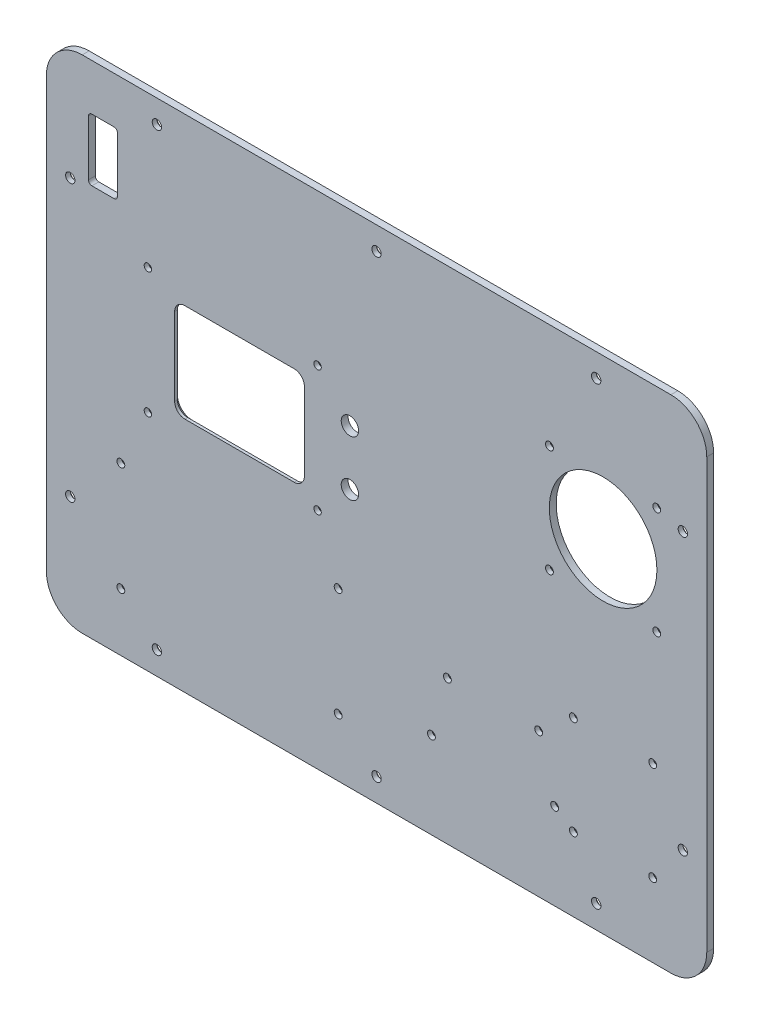
SolidWorks part; units mm, degrees
ref_plane "Front Plane" through (0, 0, 0) normal (0, 0, 1) x (1, 0, 0)
ref_plane "Top Plane" through (0, 0, 0) normal (0, 1, 0) x (1, 0, 0)
ref_plane "Right Plane" through (0, 0, 0) normal (1, 0, 0) x (0, 0, -1)
sketch "Sketch1" plane through (0, 0, 0) normal (0, 0, 1) x (1, 0, 0)
  line L0 (-151.9669, 98.7552) -> (-151.9669, -98.7552) construction
  line L1 (-135.4569, -115.2652) -> (135.4569, -115.2652) construction
  line L2 (151.9669, -98.7552) -> (151.9669, 98.7552) construction
  line L3 (135.4569, 115.2652) -> (-135.4569, 115.2652) construction
  line L4 (0, 115.2652) -> (0, 0) construction
  line L5 (0, 0) -> (151.9669, 0) construction
  line L25 (-151.9669, 98.7552) -> (-151.9669, -98.7552)
  line L27 (-135.4569, -115.2652) -> (135.4569, -115.2652)
  line L29 (151.9669, -98.7552) -> (151.9669, 98.7552)
  line L31 (135.4569, 115.2652) -> (-135.4569, 115.2652)
  arc A0 (-135.4569, -115.2652) -> (-151.9669, -98.7552) centre (-135.4569, -98.7552) cw
  arc A1 (135.4569, -115.2652) -> (151.9669, -98.7552) centre (135.4569, -98.7552) ccw
  arc A2 (151.9669, 98.7552) -> (135.4569, 115.2652) centre (135.4569, 98.7552) ccw
  arc A3 (-151.9669, 98.7552) -> (-135.4569, 115.2652) centre (-135.4569, 98.7552) cw
  arc A4 (-135.4569, -115.2652) -> (-151.9669, -98.7552) centre (-135.4569, -98.7552) cw construction
  arc A5 (135.4569, -115.2652) -> (151.9669, -98.7552) centre (135.4569, -98.7552) ccw construction
  arc A6 (151.9669, 98.7552) -> (135.4569, 115.2652) centre (135.4569, 98.7552) ccw construction
  arc A7 (-151.9669, 98.7552) -> (-135.4569, 115.2652) centre (-135.4569, 98.7552) cw construction
  dimension "D1" = 16.51
  dimension "D3" = 230.5304
  dimension "D4" = 303.9339
  dimension "D2" = 0
extrude "Boss-Extrude1" add sketch "Sketch1" against normal blind 3.175
hole_wizard "#6 Clearance Hole1" positions "Sketch2" profile "Sketch3" hole size "#6" standard "ANSI Inch" end condition up to next
sketch "Sketch2" plane through (0, 0, 0) normal (0, 0, 1) x (1, 0, 0)
  line L3 (140.9687, 63.5) -> (140.9687, -63.5) construction
  line L6 (-101.092, 104.648) -> (101.092, 104.648) construction
  line L9 (-140.9687, 63.5) -> (-140.9687, -63.5) construction
  line L10 (-101.092, -104.648) -> (101.092, -104.648) construction
  line L13 (0, -104.648) -> (0, 0) construction
  line L14 (0, 0) -> (140.9687, 0) construction
  line L17 (0, 104.648) -> (0, 0) construction
  line L18 (0, 0) -> (-140.9687, 0) construction
  point P38 (101.092, 104.648)
  point P40 (-101.092, 104.648)
  point P42 (-140.9687, 63.5)
  point P44 (-140.9687, -63.5)
  point P48 (101.092, -104.648)
  point P50 (140.9687, -63.5)
  point P52 (140.9687, 63.5)
  point P108 (-101.092, -104.648)
  point P117 (0, -104.648)
  point P125 (0, 104.648)
  dimension "D1" = 104.648
  dimension "D2" = 140.9687
  dimension "D3" = 104.648
  dimension "D4" = 140.9687
  dimension "D5" = 127
  dimension "D6" = 127
  dimension "D7" = 202.184
  dimension "D8" = 202.184
sketch "Sketch3" plane through (101.092, 104.648, 0) normal (1, 0, 0) x (0, -1, 0)
  line L0 (0, 0) -> (0, 3.175)
  line L1 (0, 3.175) -> (3.3655, 3.175)
  line L2 (2.1526, 2.1573) -> (2.1526, 0)
  line L5 (2.1526, 0) -> (0, 0)
  line L7 (3.3655, 3.175) -> (2.1526, 2.1573)
  line L8 (-3.3655, 3.175) -> (-2.1527, 2.1573) construction
  line L11 (0, -6.35) -> (0, 107.95) construction
  dimension "Thru Hole Dia." = 4.3053
  dimension "Thru Hole Depth" = 3.175
  dimension "Far C'Sink Dia." = 6.731
  dimension "Far C'Sink Angle" = 100
sketch "Sketch23" plane through (0, 0, 0) normal (0, 0, 1) x (1, 0, 0)
  line L0 (135.4569, 115.2652) -> (-135.4569, 115.2652) construction
  line L1 (151.9669, -98.7552) -> (151.9669, 98.7552) construction
  circle A0 centre (104.2657, 42.164) radius 24.765
  dimension "D1" = 49.53
  dimension "D2" = 73.1012
  dimension "D3" = 47.7012
extrude "Cut-Extrude10" cut sketch "Sketch23" against normal through all
sketch "Sketch24" plane through (0, 0, 0) normal (0, 0, 1) x (1, 0, 0)
  line L1 (-92.9119, 38.9204) -> (-33.2219, 38.9204)
  line L2 (-92.9119, 38.9204) -> (-92.9119, -6.2916)
  line L3 (-92.9119, -6.2916) -> (-33.2219, -6.2916)
  line L4 (-33.2219, 38.9204) -> (-33.2219, -6.2916)
  line L5 (-92.9119, 38.9204) -> (-33.2219, -6.2916) construction
  line L7 (-151.9669, 98.7552) -> (-151.9669, -98.7552) construction
  line L8 (-135.4569, -115.2652) -> (135.4569, -115.2652) construction
  point P4 (-63.0669, 16.3144)
  dimension "D1" = 88.9
  dimension "D2" = 131.5796
  dimension "D3" = 59.69
  dimension "D4" = 45.212
extrude "Cut-Extrude11" cut sketch "Sketch24" against normal through all
fillet "Fillet2" radius 4.699 4 edges at (-33.2219, -6.2916, -1.5875) (-92.9119, -6.2916, -1.5875) (-92.9119, 38.9204, -1.5875) (-33.2219, 38.9204, -1.5875)
chamfer "Chamfer1" distance 1.905 angle 45 8 edges at (-63.0669, -6.2916, -3.175) (-92.9119, 16.3144, -3.175) (-63.0669, 38.9204, -3.175) (-33.2219, 16.3144, -3.175) (-91.5356, -4.9153, -3.175) (-91.5356, 37.5441, -3.175) (-34.5982, -4.9153, -3.175) (-34.5982, 37.5441, -3.175)
hole_wizard "M3 Clearance Hole3" positions "Sketch29" profile "Sketch30" hole size "M3" standard "ANSI Metric" end condition up to next
sketch "Sketch29" plane through (0, 0, 0) normal (0, 0, 1) x (1, 0, 0)
  line L1 (79.57, 66.8597) -> (128.9614, 66.8597) construction
  line L2 (79.57, 66.8597) -> (79.57, 17.4683) construction
  line L3 (79.57, 17.4683) -> (128.9614, 17.4683) construction
  line L4 (128.9614, 66.8597) -> (128.9614, 17.4683) construction
  line L5 (104.2657, 66.8597) -> (104.2657, 17.4683) construction
  circle A2 centre (104.2657, 42.164) radius 34.925
  circle A3 centre (104.2657, 42.164) radius 24.765 construction
  point P0 (79.57, 66.8597)
  point P2 (128.9614, 66.8597)
  point P4 (128.9614, 17.4683)
  point P6 (79.57, 17.4683)
  dimension "D1" = 69.85
sketch "Sketch30" plane through (79.57, 66.8597, 0) normal (1, 0, 0) x (0, -1, 0)
  line L0 (0, 0) -> (0, 3.175)
  line L1 (0, 3.175) -> (2.85, 3.175)
  line L2 (1.8, 2.125) -> (1.8, 0)
  line L5 (1.8, 0) -> (0, 0)
  line L7 (2.85, 3.175) -> (1.8, 2.125)
  line L8 (-2.85, 3.175) -> (-1.8, 2.125) construction
  line L11 (0, -6.35) -> (0, 107.95) construction
  dimension "Thru Hole Dia." = 3.6
  dimension "Thru Hole Depth" = 3.175
  dimension "Far C'Sink Dia." = 5.7
  dimension "Far C'Sink Angle" = 90
hole_wizard "M3 Clearance Hole1" positions "Sketch31" profile "Sketch32" hole size "M3" standard "ANSI Metric" end condition up to next
sketch "Sketch31" plane through (0, 0, -3.175) normal (0, 0, -1) x (-1, 0, 0)
  line L1 (17.6769, -38.5952) -> (117.6769, -38.5952) construction
  line L2 (17.6769, -38.5952) -> (17.6769, -88.5952) construction
  line L3 (17.6769, -88.5952) -> (117.6769, -88.5952) construction
  line L4 (117.6769, -38.5952) -> (117.6769, -88.5952) construction
  line L5 (151.9669, 98.7552) -> (151.9669, -98.7552) construction
  line L6 (135.4569, -115.2652) -> (-135.4569, -115.2652) construction
  point P0 (17.6769, -38.5952)
  point P2 (117.6769, -38.5952)
  point P4 (117.6769, -88.5952)
  point P6 (17.6769, -88.5952)
  dimension "D1" = 100
  dimension "D2" = 50
  dimension "D3" = 34.29
  dimension "D4" = 26.67
sketch "Sketch32" plane through (-17.6769, -38.5952, -3.175) normal (1, 0, 0) x (0, 1, 0)
  line L0 (0, 0) -> (0, 3.175)
  line L1 (0, 3.175) -> (1.8, 3.175)
  line L2 (1.8, 3.175) -> (1.8, 1.05)
  line L3 (1.8, 1.05) -> (2.85, 0)
  line L5 (2.85, 0) -> (0, 0)
  line L6 (-1.8, 1.05) -> (-2.85, 0) construction
  line L11 (0, -6.35) -> (0, 107.95) construction
  dimension "Thru Hole Dia." = 3.6
  dimension "Thru Hole Depth" = 3.175
  dimension "Near C'Sink Dia." = 5.7
  dimension "Near C'Sink Angle" = 90
hole_wizard "M3 Clearance Hole2" positions "Sketch33" profile "Sketch34" hole size "M3" standard "ANSI Metric" end condition up to next
sketch "Sketch33" plane through (0, 0, 0) normal (0, 0, 1) x (1, 0, 0)
  line L0 (-135.4569, -115.2652) -> (135.4569, -115.2652) construction
  line L1 (151.9669, -98.7552) -> (151.9669, 98.7552) construction
  line L2 (25.2519, -75.5297) -> (81.9523, -75.5297) construction
  line L4 (127.0876, -35.9197) -> (127.0876, -81.4197) construction
  line L5 (127.0876, -35.9197) -> (90.5876, -35.9197) construction
  line L6 (90.5876, -35.9197) -> (90.5876, -81.4197) construction
  line L7 (90.5876, -81.4197) -> (127.0876, -81.4197) construction
  line L8 (32.6019, -49.1297) -> (74.6023, -49.1297) construction
  line L11 (53.6021, -49.1297) -> (53.6021, -75.5297) construction
  point P0 (25.2519, -75.5297)
  point P7 (81.9523, -75.5297)
  point P15 (127.0876, -81.4197)
  point P18 (127.0876, -35.9197)
  point P23 (90.5876, -81.4197)
  point P25 (90.5876, -35.9197)
  point P33 (32.6019, -49.1297)
  point P35 (74.6023, -49.1297)
  dimension "D1" = 5.89
  dimension "D2" = 26.4
  dimension "D3" = 56.7004
  dimension "D4" = 24.8793
  dimension "D5" = 33.8455
  dimension "D6" = 45.5
  dimension "D7" = 36.5
  dimension "D8" = 7.35
  dimension "D9" = 8.6353
sketch "Sketch34" plane through (25.2519, -75.5297, 0) normal (1, 0, 0) x (0, -1, 0)
  line L0 (0, 0) -> (0, 3.175)
  line L1 (0, 3.175) -> (2.85, 3.175)
  line L2 (1.8, 2.125) -> (1.8, 0)
  line L5 (1.8, 0) -> (0, 0)
  line L7 (2.85, 3.175) -> (1.8, 2.125)
  line L8 (-2.85, 3.175) -> (-1.8, 2.125) construction
  line L11 (0, -6.35) -> (0, 107.95) construction
  dimension "Thru Hole Dia." = 3.6
  dimension "Thru Hole Depth" = 3.175
  dimension "Far C'Sink Dia." = 5.7
  dimension "Far C'Sink Angle" = 90
sketch "Sketch35" plane through (0, 0, 0) normal (0, 0, 1) x (1, 0, 0)
  line L1 (-132.5994, 93.8657) -> (-119.2644, 93.8657)
  line L2 (-132.5994, 93.8657) -> (-132.5994, 65.2907)
  line L3 (-132.5994, 65.2907) -> (-119.2644, 65.2907)
  line L4 (-119.2644, 93.8657) -> (-119.2644, 65.2907)
  line L6 (-132.5994, 93.8657) -> (-119.2644, 65.2907) construction
  line L7 (-151.9669, 98.7552) -> (-151.9669, -98.7552) construction
  line L8 (135.4569, 115.2652) -> (-135.4569, 115.2652) construction
  point P4 (-125.9319, 79.5782)
  dimension "D1" = 13.335
  dimension "D2" = 28.575
  dimension "D3" = 26.035
  dimension "D4" = 35.687
extrude "Cut-Extrude12" cut sketch "Sketch35" against normal through all
fillet "Fillet1" radius 1.5875 4 edges at (-119.2644, 93.8657, -1.5875) (-119.2644, 65.2907, -1.5875) (-132.5994, 65.2907, -1.5875) (-132.5994, 93.8657, -1.5875)
hole_wizard "Ø8.0mm Dowel Hole1" positions "Sketch36" profile "Sketch37" hole size "Ø8.0" standard "ANSI Metric" end condition up to next
sketch "Sketch36" plane through (0, 0, -3.175) normal (0, 0, -1) x (-1, 0, 0)
  line L0 (31.3169, 16.3144) -> (12.2669, 16.3144) construction
  line L1 (31.3169, -1.5926) -> (31.3169, 34.2214) construction
  line L4 (12.2669, 29.0144) -> (12.2669, 3.6144) construction
  point P7 (12.2669, 29.0144)
  point P8 (12.2669, 3.6144)
  point P11 (12.2669, 16.3144)
  dimension "D1" = 25.4
  dimension "D2" = 19.05
sketch "Sketch37" plane through (-12.2669, 3.6144, -3.175) normal (1, 0, 0) x (0, 1, 0)
  line L0 (0, 0) -> (0, 3.175)
  line L1 (0, 3.175) -> (4, 3.175)
  line L2 (4, 3.175) -> (4, 0)
  line L5 (4, 0) -> (0, 0)
  line L11 (0, -6.35) -> (0, 107.95) construction
  dimension "Thru Hole Dia." = 8
  dimension "Thru Hole Depth" = 3.175
hole_wizard "M3 Clearance Hole4" positions "Sketch38" profile "Sketch39" hole size "M3" standard "ANSI Metric" end condition through all
sketch "Sketch38" plane through (0, 0, 0) normal (0, 0, 1) x (1, 0, 0)
  line L16 (-105.2309, 45.6514) -> (-27.1259, 45.6514) construction
  line L17 (-105.2309, 45.6514) -> (-105.2309, -12.1336) construction
  line L18 (-105.2309, -12.1336) -> (-27.1259, -12.1336) construction
  line L19 (-27.1259, 45.6514) -> (-27.1259, -12.1336) construction
  line L26 (-33.2219, -1.5926) -> (-33.2219, 34.2214) construction
  line L27 (-37.9209, 38.9204) -> (-88.2129, 38.9204) construction
  point P0 (-105.2309, 45.6514)
  point P2 (-27.1259, 45.6514)
  point P4 (-27.1259, -12.1336)
  point P6 (-105.2309, -12.1336)
  dimension "D1" = 78.105
  dimension "D2" = 57.785
  dimension "D3" = 6.096
  dimension "D4" = 6.731
sketch "Sketch39" plane through (-105.2309, 45.6514, 0) normal (1, 0, 0) x (0, -1, 0)
  line L0 (0, 0) -> (0, 3.175)
  line L1 (0, 3.175) -> (2.85, 3.175)
  line L2 (1.7, 2.025) -> (1.7, 0)
  line L5 (1.7, 0) -> (0, 0)
  line L7 (2.85, 3.175) -> (1.7, 2.025)
  line L8 (-2.85, 3.175) -> (-1.7, 2.025) construction
  line L11 (0, -6.35) -> (0, 107.95) construction
  dimension "Thru Hole Dia." = 3.4
  dimension "Thru Hole Depth" = 3.175
  dimension "Far C'Sink Dia." = 5.7
  dimension "Far C'Sink Angle" = 90
sketch "Sketch40" plane through (0, 0, -3.175) normal (0, 0, -1) x (-1, 0, 0)
  line L0 (94.8169, 34.2214) -> (94.8169, -1.5926) construction
  line L1 (88.2129, -8.1966) -> (37.9209, -8.1966) construction
  line L2 (31.3169, -1.5926) -> (31.3169, 34.2214) construction
  line L3 (37.9209, 40.8254) -> (88.2129, 40.8254) construction
  line L4 (94.8169, 34.2214) -> (94.8169, -1.5926)
  line L5 (88.2129, -8.1966) -> (37.9209, -8.1966)
  line L6 (31.3169, -1.5926) -> (31.3169, 34.2214)
  line L7 (37.9209, 40.8254) -> (88.2129, 40.8254)
  arc A0 (94.8169, 34.2214) -> (88.2129, 40.8254) centre (88.2129, 34.2214) ccw construction
  arc A1 (88.2129, -8.1966) -> (94.8169, -1.5926) centre (88.2129, -1.5926) ccw construction
  arc A2 (31.3169, -1.5926) -> (37.9209, -8.1966) centre (37.9209, -1.5926) ccw construction
  arc A3 (37.9209, 40.8254) -> (31.3169, 34.2214) centre (37.9209, 34.2214) ccw construction
  arc A4 (94.8169, 34.2214) -> (88.2129, 40.8254) centre (88.2129, 34.2214) ccw
  arc A5 (88.2129, -8.1966) -> (94.8169, -1.5926) centre (88.2129, -1.5926) ccw
  arc A6 (31.3169, -1.5926) -> (37.9209, -8.1966) centre (37.9209, -1.5926) ccw
  arc A7 (37.9209, 40.8254) -> (31.3169, 34.2214) centre (37.9209, 34.2214) ccw
  dimension "D3" = 6.604
  dimension "D1" = 49.022
  dimension "D2" = 63.5
